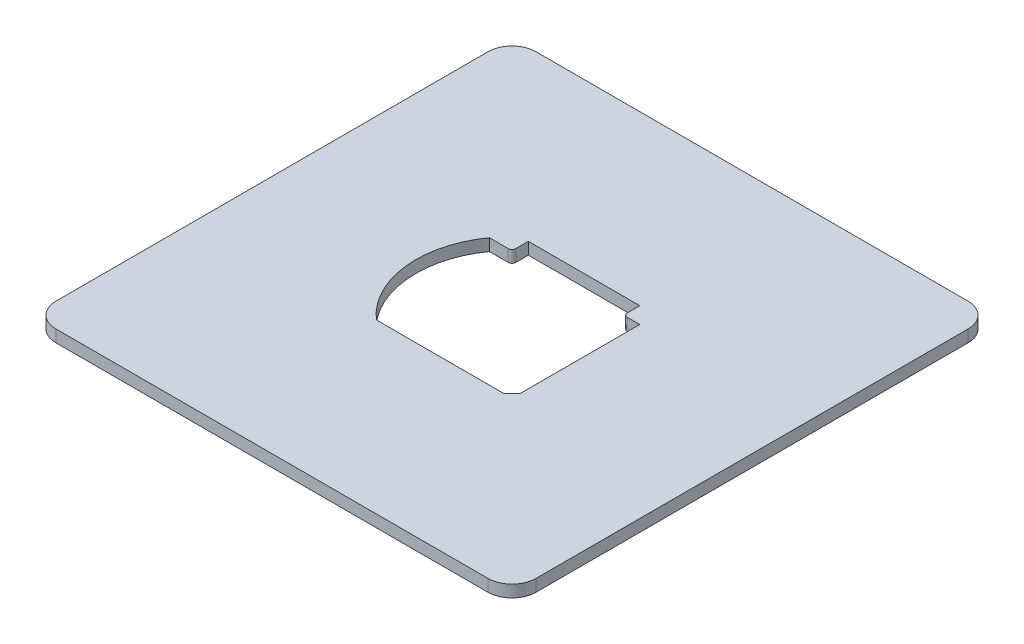
SolidWorks part; units mm, degrees
ref_plane "Front Plane" through (0, 0, 0) normal (0, 0, 1) x (1, 0, 0)
ref_plane "Top Plane" through (0, 0, 0) normal (0, 1, 0) x (1, 0, 0)
ref_plane "Right Plane" through (0, 0, 0) normal (1, 0, 0) x (0, 0, -1)
sketch "Sketch1" plane through (0, 0, 0) normal (0, 1, 0) x (1, 0, 0)
  line L0 (24.384, 41.275) -> (24.384, 39.116)
  line L1 (0, 0) -> (63.5, 0)
  line L2 (0, 0) -> (0, 63.5)
  line L3 (0, 63.5) -> (63.5, 63.5)
  line L4 (63.5, 0) -> (63.5, 63.5)
  line L5 (24.384, 39.116) -> (21.3888, 39.116)
  line L6 (39.116, 41.275) -> (39.116, 39.116)
  line L7 (39.116, 39.116) -> (41.275, 39.116)
  line L8 (23.3306, 22.225) -> (40.1694, 22.225)
  line L9 (24.384, 41.275) -> (39.116, 41.275)
  line L10 (31.75, 31.75) -> (24.384, 39.116) construction
  line L11 (41.275, 39.116) -> (41.275, 23.3306)
  line L12 (31.75, 31.75) -> (39.116, 39.116) construction
  arc A0 (21.3888, 39.116) -> (23.3306, 22.225) centre (31.75, 31.75) ccw
  arc A2 (40.1694, 22.225) -> (41.275, 23.3306) centre (31.75, 31.75) ccw
  point P7 (31.75, 0)
  point P8 (0, 31.75)
  dimension "D2" = 25.4254
  dimension "D1" = 63.5
  dimension "D3" = 14.732
  dimension "D4" = 9.525
  dimension "D5" = 9.525
  dimension "D6" = 45
  dimension "D7" = 9.525
extrude "Boss-Extrude1" add sketch "Sketch1" along normal blind 1.5875
fillet "Fillet1" radius 0.508 2 edges at (39.116, 0.7937, -39.116) (24.384, 0.7937, -39.116)
fillet "Fillet2" radius 3.175 4 edges at (63.5, 0.7937, 0) (63.5, 0.7937, -63.5) (0, 0.7937, -63.5) (0, 0.7937, 0)
